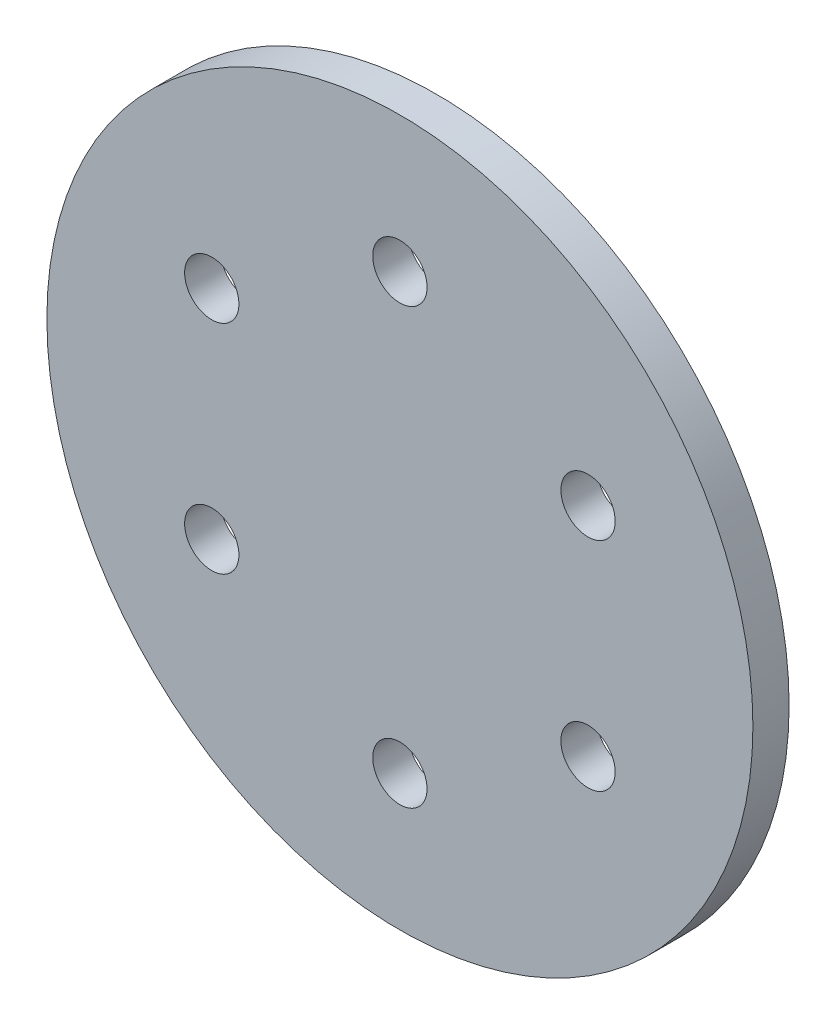
SolidWorks part; units mm, degrees
ref_plane "Front Plane" through (0, 0, 0) normal (0, 0, 1) x (1, 0, 0)
ref_plane "Top Plane" through (0, 0, 0) normal (0, 1, 0) x (1, 0, 0)
ref_plane "Right Plane" through (0, 0, 0) normal (1, 0, 0) x (0, 0, -1)
sketch "Sketch1" plane through (0, 0, 0) normal (0, 0, 1) x (1, 0, 0)
  circle A0 centre (0, 0) radius 30.9562
  circle A1 centre (0, 19.05) radius 2.3813
  circle A2 centre (16.4978, 9.525) radius 2.3813
  circle A3 centre (16.4978, -9.525) radius 2.3813
  circle A4 centre (0, -19.05) radius 2.3813
  circle A5 centre (-16.4978, -9.525) radius 2.3813
  circle A6 centre (-16.4978, 9.525) radius 2.3813
  point P17 (0, 0)
  dimension "D1" = 61.9125
  dimension "D2" = 4.7625
  dimension "D3" = 19.05
  dimension "D4" = 6
extrude "Boss-Extrude1" add sketch "Sketch1" along normal blind 3.175
